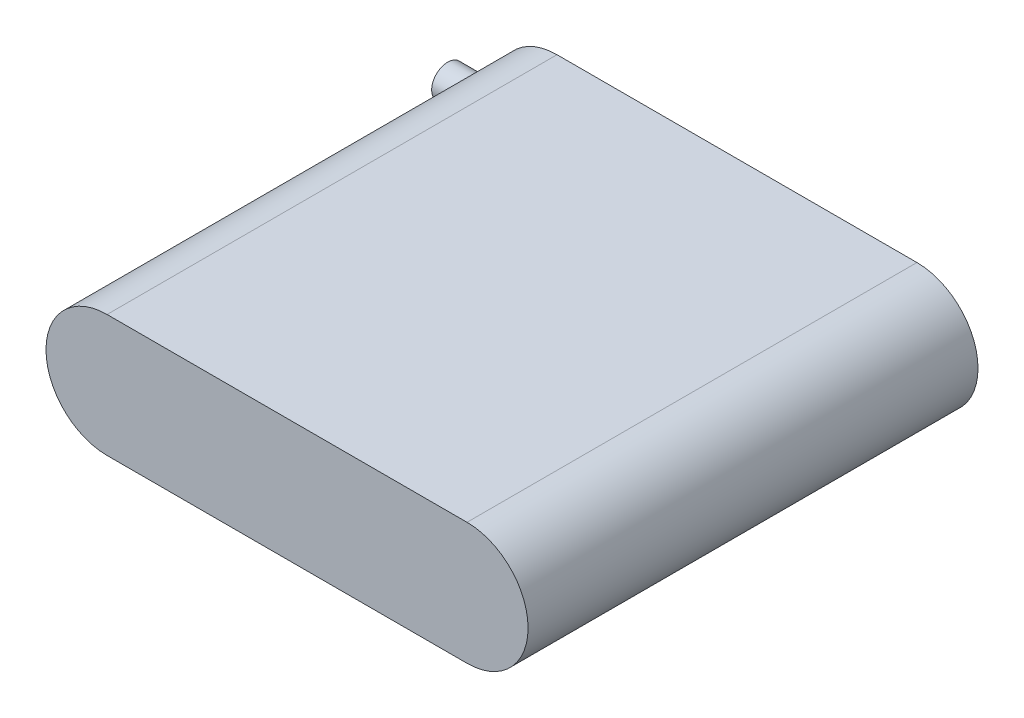
SolidWorks part; units mm, degrees
ref_plane "前视基准面" through (0, 0, 0) normal (0, 0, 1) x (1, 0, 0)
ref_plane "上视基准面" through (0, 0, 0) normal (0, 1, 0) x (1, 0, 0)
ref_plane "右视基准面" through (0, 0, 0) normal (1, 0, 0) x (0, 0, -1)
other "Configuration Table"
sketch "草图1" plane through (0, 0, 0) normal (0, 0, 1) x (1, 0, 0)
  line L0 (-54.0306, 0) -> (43.7012, 0) construction
  line L1 (0, 31.3854) -> (0, -42.1121) construction
  line L2 (-28, 0) -> (28, 0) construction
  line L5 (-28, 9.5) -> (28, 9.5)
  line L6 (-28, -9.5) -> (28, -9.5)
  arc A2 (-28, 9.5) -> (-28, -9.5) centre (-28, 0) ccw
  arc A3 (28, -9.5) -> (28, 9.5) centre (28, 0) ccw
  point P7 (0, 0)
  point P13 (37.5, 0)
  point P14 (-37.5, 0)
  dimension "D1" = 75
  dimension "D2" = 19
extrude "凸台-拉伸1" add sketch "草图1" along normal blind 70
ref_plane "基准面1" through (-37.5, 0, 0) normal (-1, 0, 0) x (0, 0, 1)
sketch "草图2" plane through (-37.5, 0, 0) normal (-1, 0, 0) x (0, 0, 1)
  line L0 (0, 9.5) -> (0, -9.5) construction
  circle A0 centre (2.5, 0) radius 2.5
  dimension "D1" = 5
extrude "凸台-拉伸3" add sketch "草图2" along normal blind 5 and the other way blind 10
